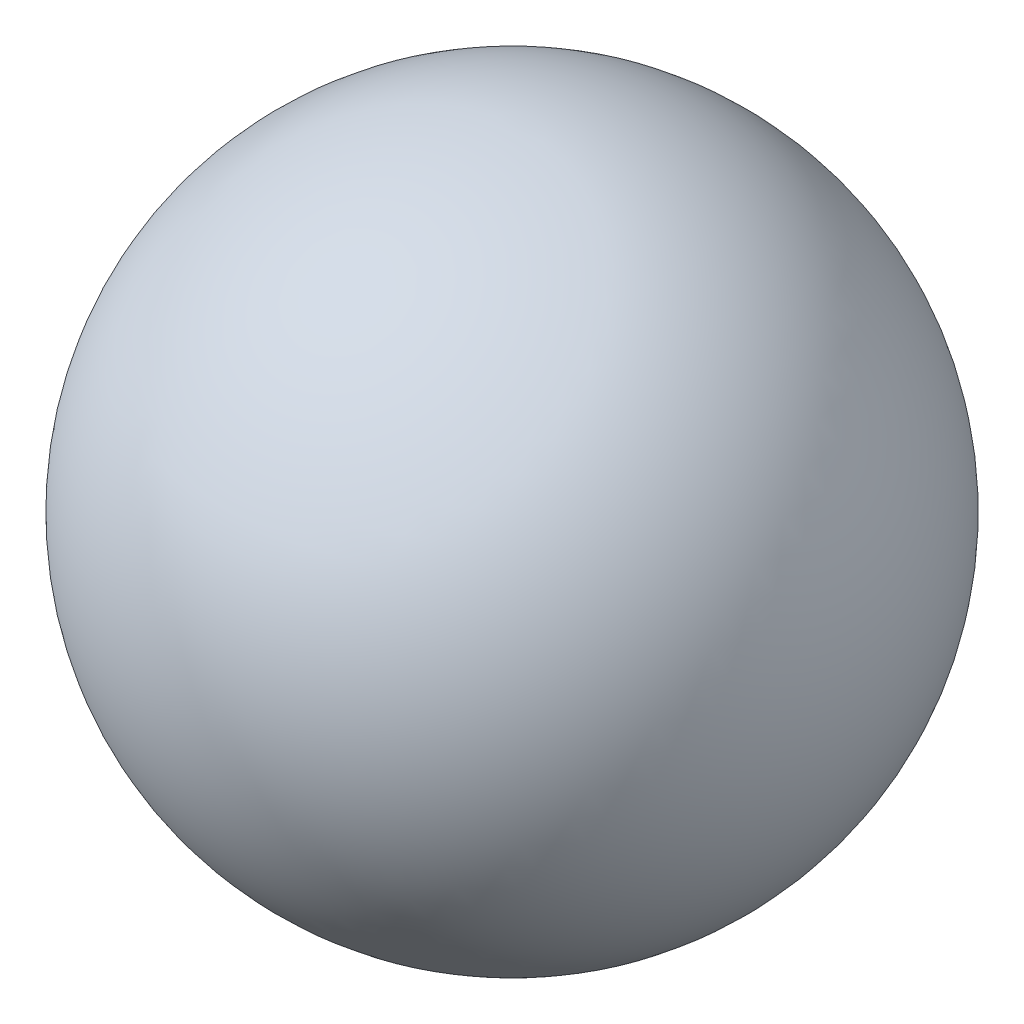
SolidWorks part; units mm, degrees
ref_plane "Front Plane" through (0, 0, 0) normal (0, 0, 1) x (1, 0, 0)
ref_plane "Top Plane" through (0, 0, 0) normal (0, 1, 0) x (1, 0, 0)
ref_plane "Right Plane" through (0, 0, 0) normal (1, 0, 0) x (0, 0, -1)
sketch "Sketch1" plane through (0, 0, 0) normal (0, 0, 1) x (1, 0, 0)
  line L0 (0, 20.75) -> (0, -20.75)
  arc A0 (0, 20.75) -> (0, -20.75) centre (0, 0) cw
  dimension "D1" = 20.75
revolve "Revolve1" add sketch "Sketch1" angle 360 about L0
